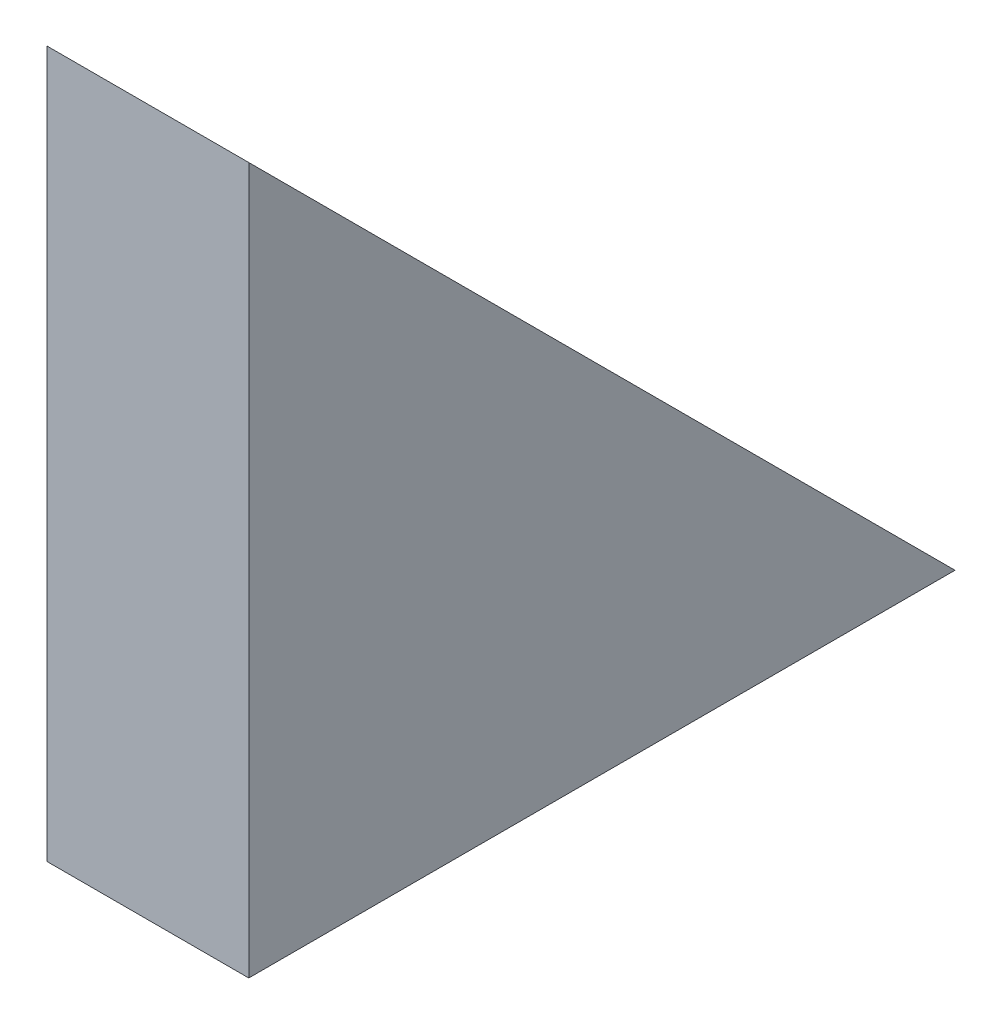
SolidWorks part; units mm, degrees
ref_plane "Front Plane" through (0, 0, 0) normal (0, 0, 1) x (1, 0, 0)
ref_plane "Top Plane" through (0, 0, 0) normal (0, 1, 0) x (1, 0, 0)
ref_plane "Right Plane" through (0, 0, 0) normal (1, 0, 0) x (0, 0, -1)
sketch "Sketch1" plane through (0, 0, 0) normal (1, 0, 0) x (0, 0, -1)
  line L0 (0, 0) -> (35, 0)
  line L1 (35, 0) -> (0, 35)
  line L2 (0, 35) -> (0, 0)
  dimension "D1" = 35
  dimension "D2" = 35
extrude "Boss-Extrude1" add sketch "Sketch1" along normal blind 10 contours L2 L0 L1
